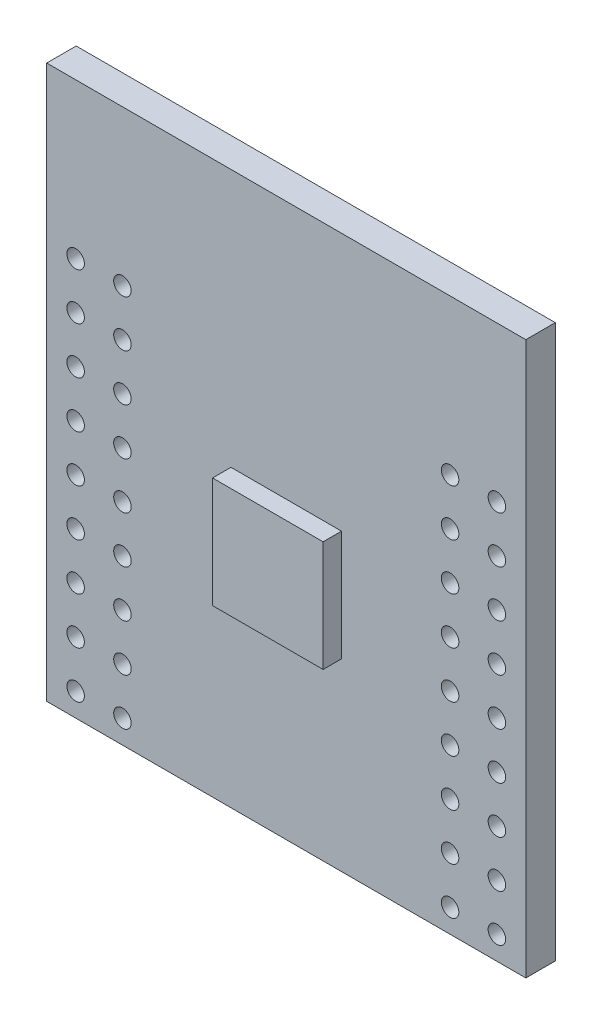
SolidWorks part; units mm, degrees
ref_plane "Front" through (0, 0, 0) normal (0, 0, 1) x (1, 0, 0)
ref_plane "Top" through (0, 0, 0) normal (0, 1, 0) x (1, 0, 0)
ref_plane "Right" through (0, 0, 0) normal (1, 0, 0) x (0, 0, -1)
sketch "草图1" plane through (0, 0, 0) normal (0, 0, 1) x (1, 0, 0)
  line L0 (0, 21.6329) -> (0, -21.5625) construction
  line L1 (-13, 15) -> (13, 15)
  line L2 (-13, 15) -> (-13, -15)
  line L3 (-13, -15) -> (13, -15)
  line L4 (13, 15) -> (13, -15)
  line L5 (-22.5551, 0) -> (19.5221, 0) construction
  dimension "D1" = 30
  dimension "D2" = 26
extrude "凸台-拉伸1" add sketch "草图1" against normal blind 1.6
sketch "草图2" plane through (0, 0, 0) normal (0, 0, 1) x (1, 0, 0)
  line L0 (-25.6235, 0) -> (24.9968, 0) construction
  line L1 (0, 25.4038) -> (0, -28.8958) construction
  line L2 (-13, -15) -> (13, -15) construction
  line L3 (-3, 1) -> (3, 1)
  line L4 (-3, 1) -> (-3, -5)
  line L5 (-3, -5) -> (3, -5)
  line L6 (3, 1) -> (3, -5)
  dimension "D1" = 10
  dimension "D2" = 6
  dimension "D3" = 6
extrude "凸台-拉伸2" add sketch "草图2" along normal blind 1
sketch "草图3" plane through (0, 0, 0) normal (0, 0, 1) x (1, 0, 0)
  line L0 (-13, -15) -> (13, -15) construction
  line L2 (0, 20.122) -> (0, -36.382) construction
  circle A0 centre (-11.43, -13.73) radius 0.475
  circle A1 centre (11.43, -13.73) radius 0.475
  circle A2 centre (-8.89, -13.73) radius 0.475
  circle A3 centre (8.89, -13.73) radius 0.475
  dimension "D1" = 0.95
  dimension "D2" = 1.27
  dimension "D3" = 22.86
  dimension "D4" = 2.54
  dimension "D5" = 2.54
ref_plane "基准面1" through (0, 0, 0) normal (1, 0, 0) x (0, 0, -1)
ref_plane "基准面2" through (0, 0, -1.6) normal (0, 0, -1) x (-1, 0, 0)
extrude "切除-拉伸1" cut sketch "草图3" against normal up to next
pattern_linear "阵列(线性)2" count 9 spacing 2.54 along (0, 1, 0) of "切除-拉伸1"
